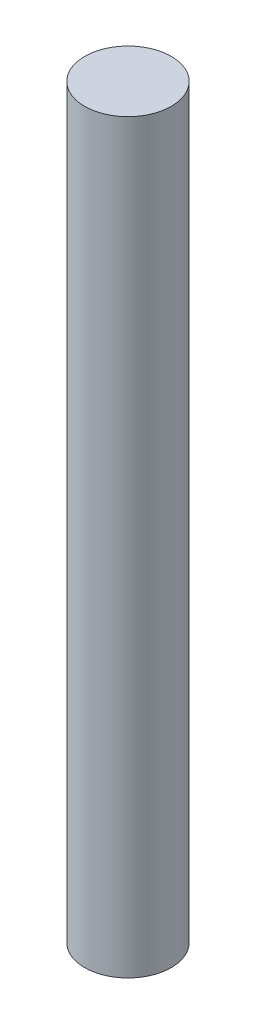
SolidWorks part; units mm, degrees
ref_plane "Front Plane" through (0, 0, 0) normal (0, 0, 1) x (1, 0, 0)
ref_plane "Top Plane" through (0, 0, 0) normal (0, 1, 0) x (1, 0, 0)
ref_plane "Right Plane" through (0, 0, 0) normal (1, 0, 0) x (0, 0, -1)
sketch "Sketch1" plane through (0, 0, 0) normal (0, 1, 0) x (1, 0, 0)
  circle A0 centre (0, 0) radius 5.1594
  dimension "D1" = 10.3187
extrude "Boss-Extrude1" add sketch "Sketch1" along normal blind 88.9
